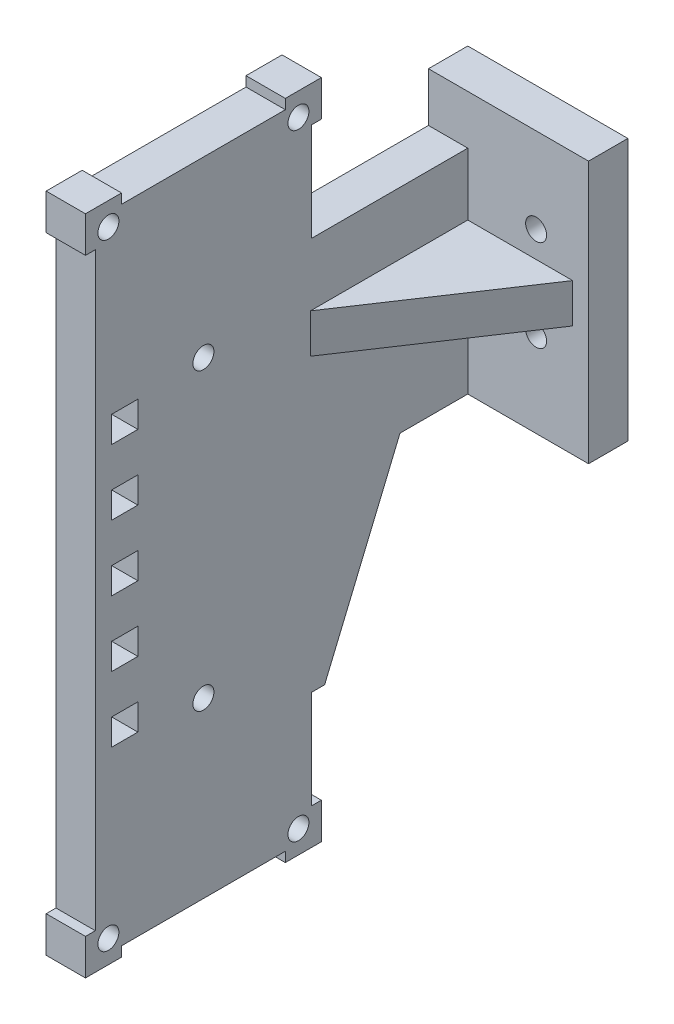
SolidWorks part; units mm, degrees
ref_plane "前视基准面" through (0, 0, 0) normal (0, 0, 1) x (1, 0, 0)
ref_plane "上视基准面" through (0, 0, 0) normal (0, 1, 0) x (1, 0, 0)
ref_plane "右视基准面" through (0, 0, 0) normal (1, 0, 0) x (0, 0, -1)
other "Configuration Table"
sketch3d "3D草图1"
  point P0 (193.15, 0, 0)
  point P1 (193.15, 0, -10)
  point P2 (193.15, 10, 0)
ref_plane "基准面1" through (193.15, 0, 0) normal (1, 0, 0) x (0, 0, -1)
sketch "草图1" plane through (193.15, 0, 0) normal (1, 0, 0) x (0, 0, -1)
  line L0 (-82, -62.5) -> (-82, -68)
  line L1 (-82, -68) -> (-87.5, -68)
  line L2 (-87.5, -68) -> (-87.5, -66.5)
  line L3 (-87.5, -66.5) -> (-112.5, -66.5)
  line L4 (-112.5, -66.5) -> (-112.5, -68)
  line L5 (-112.5, -68) -> (-118, -68)
  line L6 (-118, -68) -> (-118, -62.5)
  line L7 (-118, -62.5) -> (-116.5, -62.5)
  line L8 (-116.5, -62.5) -> (-116.5, 27.5)
  line L9 (-116.5, 27.5) -> (-118, 27.5)
  line L10 (-118, 27.5) -> (-118, 33)
  line L11 (-118, 33) -> (-112.5, 33)
  line L12 (-112.5, 33) -> (-112.5, 31.5)
  line L13 (-112.5, 31.5) -> (-87.5, 31.5)
  line L14 (-87.5, 31.5) -> (-87.5, 33)
  line L15 (-87.5, 33) -> (-82, 33)
  line L16 (-82, 33) -> (-82, 27.5)
  line L17 (-82, 27.5) -> (-83.5, 27.5)
  line L18 (-83.5, 27.5) -> (-83.5, -62.5)
  line L19 (-83.5, -62.5) -> (-82, -62.5)
extrude "凸台-拉伸1" add sketch "草图1" along normal blind 6
sketch3d "3D草图2"
  point P0 (193.15, 0, 0)
  point P1 (193.15, 0, -10)
  point P2 (193.15, 10, 0)
ref_plane "基准面2" through (193.15, 0, 0) normal (1, 0, 0) x (0, 0, -1)
sketch "草图2" plane through (193.15, 0, 0) normal (1, 0, 0) x (0, 0, -1)
  circle A0 centre (-85.5, -64.5) radius 1.6
  circle A1 centre (-114.5, -64.5) radius 1.6
  circle A2 centre (-85.5, 29.5) radius 1.6
  circle A3 centre (-114.5, 29.5) radius 1.6
extrude "切除-拉伸1" cut sketch "草图2" along normal blind 6
sketch3d "3D草图3"
  point P0 (193.15, 0, 0)
  point P1 (193.15, 0, -10)
  point P2 (193.15, 10, 0)
ref_plane "基准面3" through (193.15, 0, 0) normal (1, 0, 0) x (0, 0, -1)
sketch "草图3" plane through (193.15, 0, 0) normal (1, 0, 0) x (0, 0, -1)
  line L0 (-81, -47.5) -> (-81, 12.5)
  line L1 (-81, 12.5) -> (-107, 12.5)
  line L2 (-107, 12.5) -> (-107, -47.5)
  line L3 (-107, -47.5) -> (-81, -47.5)
extrude "切除-拉伸2" cut sketch "草图3" along normal blind 6
sketch3d "3D草图4"
  point P0 (193.15, 0, 0)
  point P1 (193.15, 0, -10)
  point P2 (193.15, 10, 0)
ref_plane "基准面4" through (193.15, 0, 0) normal (1, 0, 0) x (0, 0, -1)
sketch "草图4" plane through (193.15, 0, 0) normal (1, 0, 0) x (0, 0, -1)
  line L0 (-110, -39.5) -> (-110, -35.5)
  line L1 (-110, -35.5) -> (-114, -35.5)
  line L2 (-114, -35.5) -> (-114, -39.5)
  line L3 (-114, -39.5) -> (-110, -39.5)
  line L4 (-110, -29.5) -> (-110, -25.5)
  line L5 (-110, -25.5) -> (-114, -25.5)
  line L6 (-114, -25.5) -> (-114, -29.5)
  line L7 (-114, -29.5) -> (-110, -29.5)
  line L8 (-110, -19.5) -> (-110, -15.5)
  line L9 (-110, -15.5) -> (-114, -15.5)
  line L10 (-114, -15.5) -> (-114, -19.5)
  line L11 (-114, -19.5) -> (-110, -19.5)
  line L12 (-110, -9.5) -> (-110, -5.5)
  line L13 (-110, -5.5) -> (-114, -5.5)
  line L14 (-114, -5.5) -> (-114, -9.5)
  line L15 (-114, -9.5) -> (-110, -9.5)
  line L16 (-110, 0.5) -> (-110, 4.5)
  line L17 (-110, 4.5) -> (-114, 4.5)
  line L18 (-114, 4.5) -> (-114, 0.5)
  line L19 (-114, 0.5) -> (-110, 0.5)
extrude "切除-拉伸3" cut sketch "草图4" along normal blind 6
sketch3d "3D草图5"
  point P0 (0, 0, 53.6561)
  point P1 (10, 0, 53.6561)
  point P2 (0, 10, 53.6561)
ref_plane "基准面5" through (0, 0, 53.6561) normal (0, 0, 1) x (1, 0, 0)
sketch "草图5" plane through (0, 0, 53.6561) normal (0, 0, 1) x (1, 0, 0)
  line L0 (193.15, -47.5) -> (217.5786, -47.5)
  line L1 (193.15, -47.5) -> (193.15, 28)
  line L2 (193.15, 28) -> (217.5786, 28)
  line L3 (217.5786, -47.5) -> (217.5786, 28)
extrude "凸台-拉伸2" add sketch "草图5" along normal blind 6
sketch3d "3D草图6"
  point P0 (0, 0, 53.6561)
  point P1 (10, 0, 53.6561)
  point P2 (0, 10, 53.6561)
ref_plane "基准面6" through (0, 0, 53.6561) normal (0, 0, 1) x (1, 0, 0)
sketch "草图6" plane through (0, 0, 53.6561) normal (0, 0, 1) x (1, 0, 0)
  line L0 (193.15, -47.5) -> (199.15, -47.5)
  line L1 (193.15, -47.5) -> (193.15, 12.5)
  line L2 (193.15, 12.5) -> (199.15, 12.5)
  line L3 (199.15, -47.5) -> (199.15, 12.5)
extrude "凸台-拉伸3" add sketch "草图6" along normal blind 54.3439
sketch3d "3D草图7"
  point P0 (0, 0, 59.6561)
  point P1 (10, 0, 59.6561)
  point P2 (0, 10, 59.6561)
ref_plane "基准面7" through (0, 0, 59.6561) normal (0, 0, 1) x (1, 0, 0)
sketch "草图7" plane through (0, 0, 59.6561) normal (0, 0, 1) x (1, 0, 0)
  circle A0 centre (209.5786, -7) radius 1.6
  circle A1 centre (209.5786, 7) radius 1.6
extrude "切除-拉伸4" cut sketch "草图7" against normal blind 6
sketch3d "3D草图8"
  point P0 (199.15, 0, 0)
  point P1 (199.15, 0, -10)
  point P2 (199.15, 10, 0)
ref_plane "基准面8" through (199.15, 0, 0) normal (1, 0, 0) x (0, 0, -1)
sketch "草图8" plane through (199.15, 0, 0) normal (1, 0, 0) x (0, 0, -1)
  circle A0 centre (-100, -40) radius 1.6
  circle A1 centre (-100, 5) radius 1.6
extrude "切除-拉伸5" cut sketch "草图8" against normal blind 6
sketch3d "3D草图9"
  point P0 (0, -38.5, 0)
  point P1 (10, -38.5, 0)
  point P2 (0, -38.5, -10)
ref_plane "基准面9" through (0, -38.5, 0) normal (0, 1, 0) x (1, 0, 0)
sketch "草图9" plane through (0, -38.5, 0) normal (0, 1, 0) x (1, 0, 0)
  line L0 (199.15, -59.6561) -> (215.15, -59.6561)
  line L1 (215.15, -59.6561) -> (199.15, -83.6561)
  line L2 (199.15, -83.6561) -> (199.15, -59.6561)
sketch3d "3D草图10"
  point P0 (0, -3, 0)
  point P1 (10, -3, 0)
  point P2 (0, -3, -10)
ref_plane "基准面10" through (0, -3, 0) normal (0, 1, 0) x (1, 0, 0)
sketch "草图10" plane through (0, -3, 0) normal (0, 1, 0) x (1, 0, 0)
  line L0 (199.15, -59.6561) -> (215.15, -59.6561)
  line L1 (215.15, -59.6561) -> (199.15, -83.6561)
  line L2 (199.15, -83.6561) -> (199.15, -59.6561)
extrude "凸台-拉伸5" add sketch "草图10" along normal blind 6
sketch "草图11" plane through (0, 0, 59.6561) normal (0, 0, 1) x (1, 0, 0)
  circle A0 centre (209.5786, 7) radius 1.6
  circle A1 centre (209.5786, -7) radius 1.6
sketch3d "3D草图11"
  point P0 (0, 0, 50)
  point P1 (10, 0, 50)
  point P2 (0, 10, 50)
ref_plane "基准面11" through (0, 0, 50) normal (0, 0, 1) x (1, 0, 0)
sketch "草图12" plane through (0, 0, 50) normal (0, 0, 1) x (1, 0, 0)
  line L0 (190, -80) -> (220, -80)
  line L1 (220, -80) -> (220, -12)
  line L2 (220, -12) -> (190, -12)
  line L3 (190, -12) -> (190, -80)
sketch3d "3D草图12"
  point P0 (0, 0, 50)
  point P1 (10, 0, 50)
  point P2 (0, 10, 50)
ref_plane "基准面12" through (0, 0, 50) normal (0, 0, 1) x (1, 0, 0)
sketch "草图13" plane through (0, 0, 50) normal (0, 0, 1) x (1, 0, 0)
  line L0 (190, 12) -> (220, 12)
  line L1 (220, 12) -> (220, 50)
  line L2 (220, 50) -> (190, 50)
  line L3 (190, 50) -> (190, 12)
sketch3d "3D草图13"
  point P0 (190, 0, 0)
  point P1 (190, 10, 0)
  point P2 (190, 0, 10)
ref_plane "基准面13" through (190, 0, 0) normal (1, 0, 0) x (0, 0, -1)
sketch "草图14" plane through (190, 0, 0) normal (1, 0, 0) x (0, 0, -1)
  line L0 (-70, -47.5) -> (-81.5, -47.5)
  line L1 (-81.5, -47.5) -> (-70, -12)
  line L2 (-70, -12) -> (-70, -47.5)
sketch3d "3D草图14"
  point P0 (0, 0, 50)
  point P1 (10, 0, 50)
  point P2 (0, 10, 50)
ref_plane "基准面14" through (0, 0, 50) normal (0, 0, 1) x (1, 0, 0)
sketch "草图15" plane through (0, 0, 50) normal (0, 0, 1) x (1, 0, 0)
  line L0 (190, -80) -> (220, -80)
  line L1 (220, -80) -> (220, -20)
  line L2 (220, -20) -> (190, -20)
  line L3 (190, -20) -> (190, -80)
extrude "切除-拉伸6" cut sketch "草图15" along normal blind 20
sketch3d "3D草图15"
  point P0 (0, 0, 50)
  point P1 (10, 0, 50)
  point P2 (0, 10, 50)
ref_plane "基准面15" through (0, 0, 50) normal (0, 0, 1) x (1, 0, 0)
sketch "草图16" plane through (0, 0, 50) normal (0, 0, 1) x (1, 0, 0)
  line L0 (190, 20) -> (220, 20)
  line L1 (220, 20) -> (220, 50)
  line L2 (220, 50) -> (190, 50)
  line L3 (190, 50) -> (190, 20)
extrude "切除-拉伸7" cut sketch "草图16" along normal blind 20
sketch3d "3D草图16"
  point P0 (190, 0, 0)
  point P1 (190, 10, 0)
  point P2 (190, 0, 10)
ref_plane "基准面16" through (190, 0, 0) normal (1, 0, 0) x (0, 0, -1)
sketch "草图17" plane through (190, 0, 0) normal (1, 0, 0) x (0, 0, -1)
  line L0 (-70, -47.5) -> (-81.5, -47.5)
  line L1 (-81.5, -47.5) -> (-70, -20)
  line L2 (-70, -20) -> (-70, -47.5)
extrude "切除-拉伸8" cut sketch "草图17" along normal blind 10
